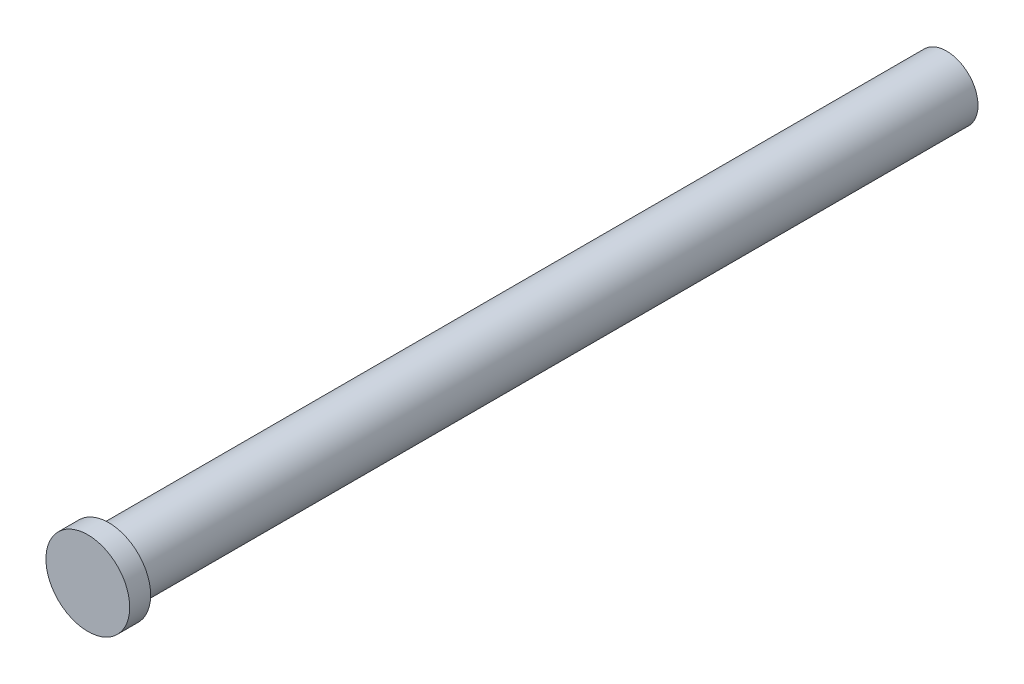
SolidWorks part; units mm, degrees
ref_plane "Plan de face" through (0, 0, 0) normal (0, 0, 1) x (1, 0, 0)
ref_plane "Plan de dessus" through (0, 0, 0) normal (0, 1, 0) x (1, 0, 0)
ref_plane "Plan de droite" through (0, 0, 0) normal (1, 0, 0) x (0, 0, -1)
sketch "Esquisse1" plane through (0, 0, 0) normal (0, 0, 1) x (1, 0, 0)
  circle A0 centre (0, 0) radius 3
extrude "Boss.-Extru.1" add sketch "Esquisse1" along normal blind 80
sketch "Esquisse2" plane through (0, 0, 80) normal (0, 0, 1) x (1, 0, 0)
  circle A0 centre (0, 0) radius 4
extrude "Boss.-Extru.2" add sketch "Esquisse2" along normal blind 2
